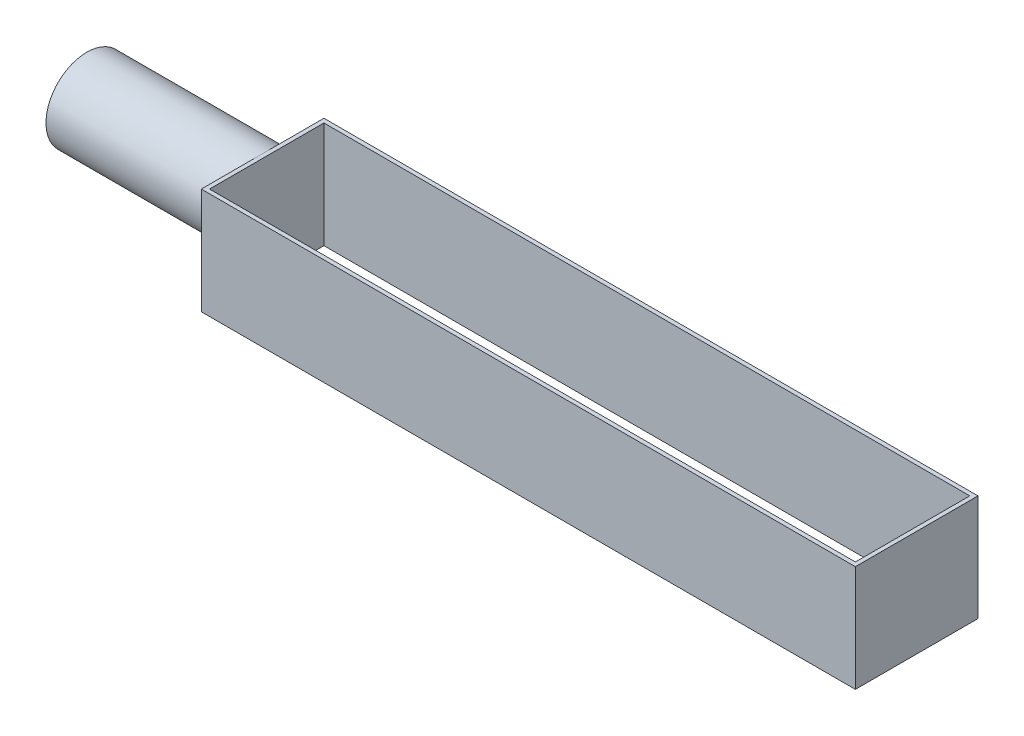
SolidWorks part; units mm, degrees
material "Stainless Steel (ferritic)"
ref_plane "Front Plane" through (0, 0, 0) normal (0, 0, 1) x (1, 0, 0)
ref_plane "Top Plane" through (0, 0, 0) normal (0, 1, 0) x (1, 0, 0)
ref_plane "Right Plane" through (0, 0, 0) normal (1, 0, 0) x (0, 0, -1)
sketch "Sketch1" plane through (0, 0, 0) normal (1, 0, 0) x (0, 0, -1)
  circle A0 centre (0, 0) radius 5
  dimension "D1" = 10
extrude "Boss-Extrude1" add sketch "Sketch1" along normal blind 22
sketch "Sketch2" plane through (0, 0, 0) normal (0, 1, 0) x (1, 0, 0)
  line L0 (0, 0) -> (132.9436, 0) construction
  line L1 (22, -5) -> (22, 5) construction
  line L2 (101.5, -7.5) -> (21.5, -7.5)
  line L3 (101.5, -7.5) -> (101.5, 7.5)
  line L4 (101.5, 7.5) -> (21.5, 7.5)
  line L5 (21.5, -7.5) -> (21.5, 7.5)
  line L6 (101.5, -7.5) -> (21.5, 7.5) construction
  line L7 (101.5, 7.5) -> (21.5, -7.5) construction
  line L8 (101, -7) -> (22, -7)
  line L9 (101, -7) -> (101, 7)
  line L10 (101, 7) -> (22, 7)
  line L11 (22, -7) -> (22, 7)
  line L12 (101, -7) -> (22, 7) construction
  line L13 (101, 7) -> (22, -7) construction
  point P3 (61.5, 0)
  point P8 (61.5, 0)
  dimension "D1" = 0.5
  dimension "D2" = 15
  dimension "D3" = 80
  dimension "D4" = 0.5
extrude "Boss-Extrude2" add sketch "Sketch2" along normal blind 5 and the other way blind 8
